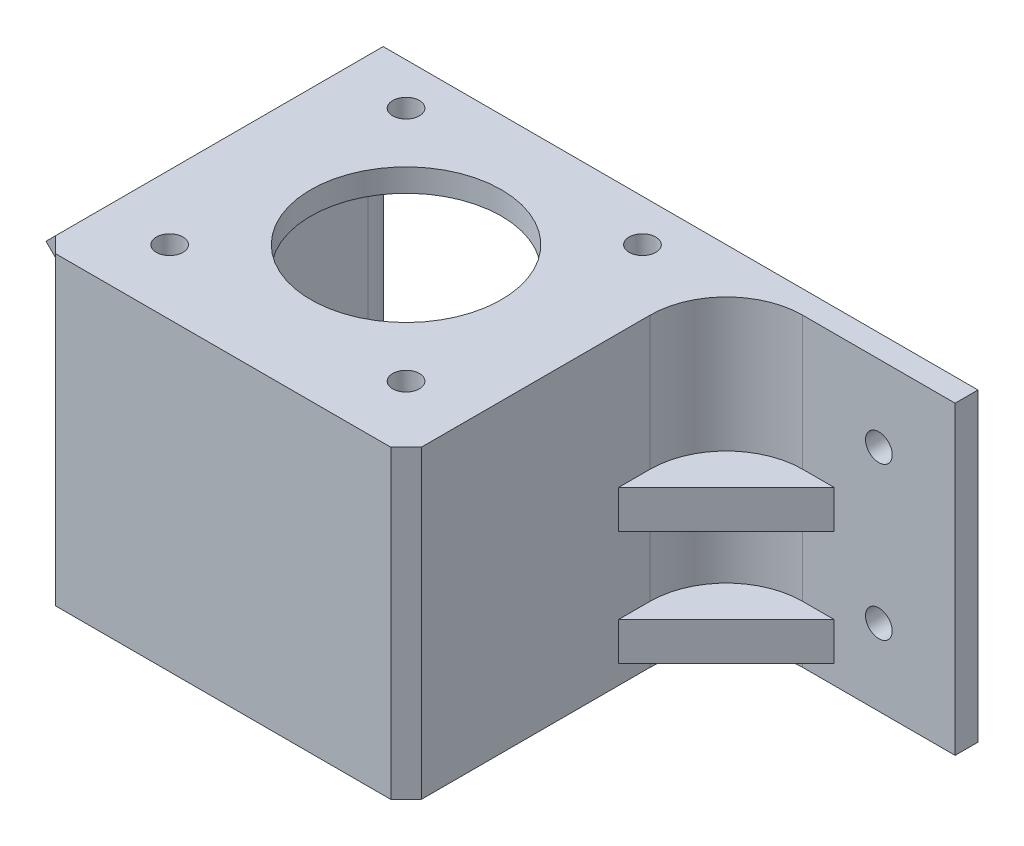
SolidWorks part; units mm, degrees
ref_plane "Front Plane" through (0, 0, 0) normal (0, 0, 1) x (1, 0, 0)
ref_plane "Top Plane" through (0, 0, 0) normal (0, 1, 0) x (1, 0, 0)
ref_plane "Right Plane" through (0, 0, 0) normal (1, 0, 0) x (0, 0, -1)
sketch "Sketch1" plane through (0, 0, 0) normal (0, 1, 0) x (1, 0, 0)
  line L0 (-24, 21) -> (-24, -24)
  line L1 (-21, 21) -> (21, 21) construction
  line L2 (-21, 21) -> (-21, -21) construction
  line L3 (-21, -21) -> (21, -21) construction
  line L4 (21, 21) -> (21, -21) construction
  line L5 (-21, 21) -> (21, -21) construction
  line L6 (-21, -21) -> (21, 21) construction
  line L7 (-24, -24) -> (24, -24)
  line L8 (24, 21) -> (24, -24)
  line L9 (-24, 21) -> (24, 21)
  point P0 (0, 0)
  dimension "D1" = 42
  dimension "D2" = 3
extrude "Boss-Extrude1" add sketch "Sketch1" along normal blind 3
sketch "Sketch2" plane through (0, 0, 0) normal (0, -1, 0) x (1, 0, 0)
  line L1 (-21, 21) -> (21, 21)
  line L2 (-21, 21) -> (-21, -21)
  line L4 (21, 21) -> (21, -21)
  line L5 (-21, 21) -> (21, -21) construction
  line L6 (-21, -21) -> (21, 21) construction
  line L7 (24, -21) -> (-24, -21) construction
  line L8 (21, -21) -> (24, -21)
  line L9 (-24, 24) -> (24, 24)
  line L10 (-24, 24) -> (-24, -21)
  line L11 (-24, -21) -> (-21, -21)
  line L12 (24, 24) -> (24, -21)
  point P0 (0, 0)
  dimension "D1" = 42
extrude "Boss-Extrude2" add sketch "Sketch2" along normal blind 37
sketch "Sketch3" plane through (24, 0, 0) normal (1, 0, 0) x (0, 0, -1)
  line L0 (21, -37) -> (-24, -37) construction
  line L1 (21, 3) -> (18, 3)
  line L2 (21, 3) -> (21, -37)
  line L3 (21, -37) -> (18, -37)
  line L4 (18, 3) -> (18, -37)
  dimension "D1" = 3
extrude "Boss-Extrude3" add sketch "Sketch3" along normal blind 30
sketch "Sketch4" plane through (0, 0, -21) normal (0, 0, -1) x (-1, 0, 0)
  line L0 (24, 3) -> (65.2132, -38.2132)
  line L1 (65.2132, -38.2132) -> (45.2132, -58.2132)
  line L2 (45.2132, -58.2132) -> (24, -37)
  line L3 (24, 3) -> (24, -37) construction
  line L4 (24, 3) -> (24, -37)
  dimension "D1" = 45
  dimension "D2" = 30
extrude "Boss-Extrude4" add sketch "Sketch4" against normal blind 3
fillet "Fillet1" radius 10 2 edges at (-24, -17, -18) (24, -17, -18)
fillet "Fillet2" radius 5 2 edges at (-21, -18.5, -21) (21, -18.5, -21)
chamfer "Chamfer1" distance 2 angle 45 2 edges at (-24, -17, 24) (24, -17, 24)
sketch "Sketch5" plane through (0, 0, 0) normal (0, -1, 0) x (1, 0, 0)
  line L7 (-15.5, 15.5) -> (15.5, 15.5) construction
  line L8 (-15.5, 15.5) -> (-15.5, -15.5) construction
  line L9 (-15.5, -15.5) -> (15.5, -15.5) construction
  line L10 (15.5, 15.5) -> (15.5, -15.5) construction
  line L11 (-15.5, 15.5) -> (15.5, -15.5) construction
  line L12 (-15.5, -15.5) -> (15.5, 15.5) construction
  circle A0 centre (-15.5, 15.5) radius 1.75
  circle A1 centre (15.5, 15.5) radius 1.75
  circle A2 centre (15.5, -15.5) radius 1.75
  circle A3 centre (-15.5, -15.5) radius 1.75
  circle A4 centre (0, 0) radius 12.5
  point P0 (0, 0)
  dimension "D2" = 4
  dimension "D3" = 3.5
  dimension "D4" = 25
  dimension "D1" = 31
extrude "Cut-Extrude1" cut sketch "Sketch5" against normal through all
ref_plane "Plane1" through (0, -17, 0) normal (0, 1, 0) x (1, 0, 0)
sketch "Sketch6" plane through (0, -17, 0) normal (0, 1, 0) x (1, 0, 0)
  line L0 (-24, 3.8579) -> (-38.1421, 18)
  line L1 (-24, 8) -> (-24, -22) construction
  line L2 (-65.2132, 18) -> (-34, 18) construction
  dimension "D1" = 45
  dimension "D2" = 20
rib "Rib2" sketch "Sketch6" sketch "Sketch6" thickness 5 extrusion direction parallel to sketch draft on no parameters "D1"=5
pattern_linear "LPattern2" count 2 spacing 15 along (0, -1, 0) of "Rib2"
mirror "Mirror1" about plane through (0, 0, 0) normal (1, 0, 0) of "LPattern2", "Rib2"
sketch "Sketch7" plane through (0, 0, -18) normal (0, 0, 1) x (1, 0, 0)
  line L0 (44, 3) -> (44, -37) construction
  line L1 (54, 3) -> (34, 3) construction
  line L2 (54, -37) -> (34, -37) construction
  line L3 (-49.6066, -22.6066) -> (-29.6066, -42.6066) construction
  line L4 (-65.2132, -38.2132) -> (-34, -7) construction
  line L5 (-34, -47) -> (-24, -37) construction
  line L6 (-45.2132, -58.2132) -> (-65.2132, -38.2132) construction
  line L7 (-49.6066, -22.6066) -> (-65.2132, -38.2132) construction
  line L8 (-57.4099, -30.4099) -> (-37.4099, -50.4099) construction
  line L9 (-34, -47) -> (-45.2132, -58.2132) construction
  circle A0 centre (44, -7) radius 1.75
  circle A1 centre (44, -27) radius 1.75
  circle A2 centre (-50.3388, -37.481) radius 1.75
  dimension "D1" = 10
  dimension "D3" = 3.5
  dimension "D4" = 3.5
  dimension "D5" = 3.5
  dimension "D2" = 10
  dimension "D6" = 10
extrude "Cut-Extrude2" cut sketch "Sketch7" against normal through all
